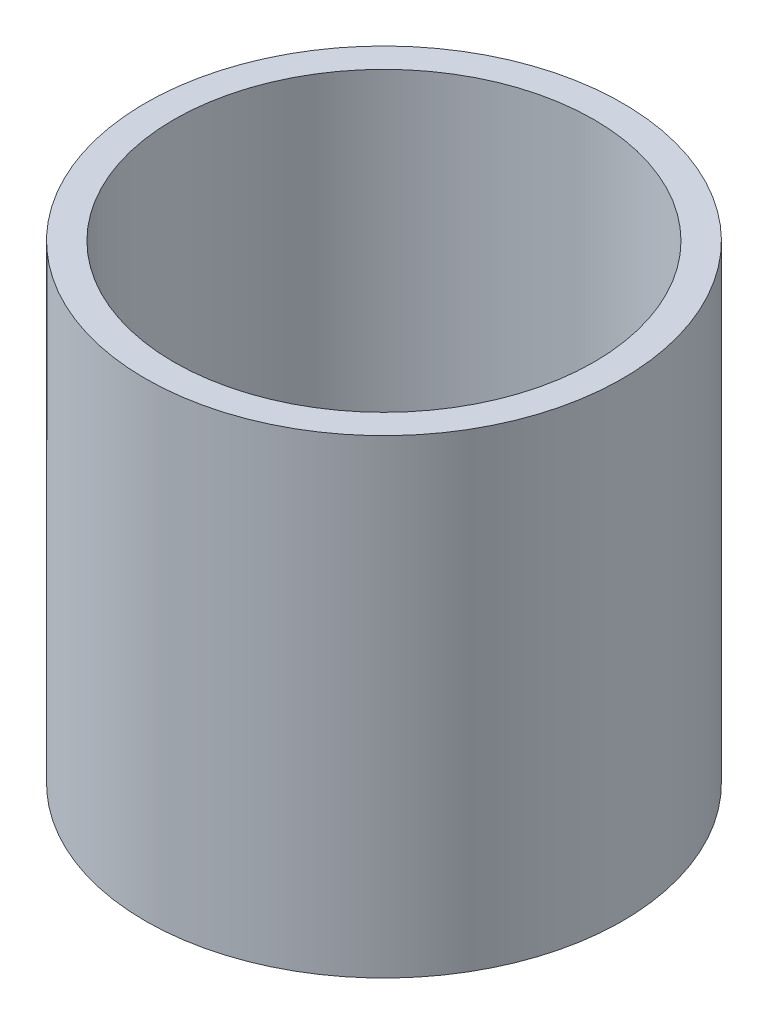
SolidWorks part; units mm, degrees
material "PVC Rigid"
ref_plane "Front Plane" through (0, 0, 0) normal (0, 0, 1) x (1, 0, 0)
ref_plane "Top Plane" through (0, 0, 0) normal (0, 1, 0) x (1, 0, 0)
ref_plane "Right Plane" through (0, 0, 0) normal (1, 0, 0) x (0, 0, -1)
sketch "Sketch1" plane through (0, 0, 0) normal (0, 1, 0) x (1, 0, 0)
  circle A0 centre (0, 0) radius 50.8
  circle A1 centre (0, 0) radius 44.7167
  dimension "D1" = 101.6
  dimension "D2" = 89.4334
extrude "Boss-Extrude1" add sketch "Sketch1" along normal blind 100
sketch "Sketch2" plane through (0, 100, 0) normal (0, 1, 0) x (1, 0, 0)
  circle A0 centre (0, 0) radius 44.7167 construction
  circle A1 centre (0, 0) radius 44.7167
